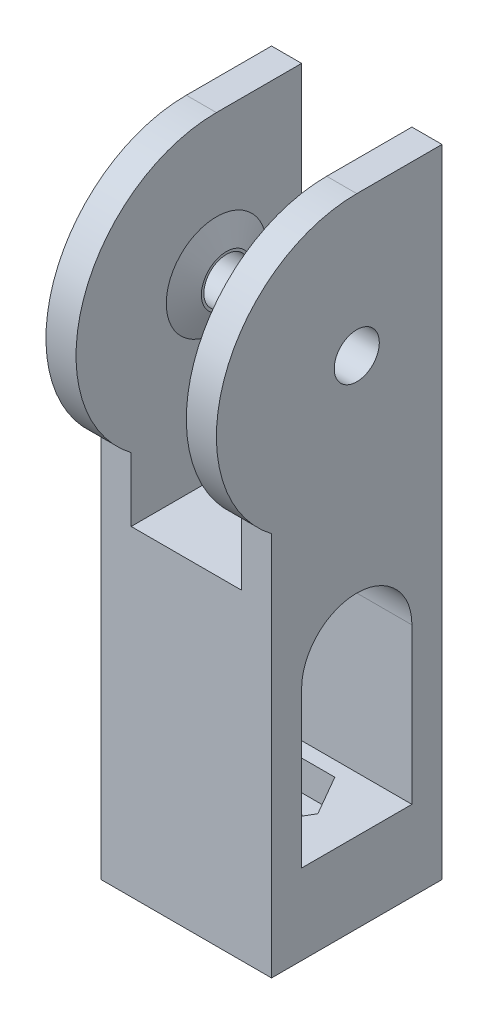
SolidWorks part; units mm, degrees
ref_plane "Front Plane" through (0, 0, 0) normal (0, 0, 1) x (1, 0, 0)
ref_plane "Top Plane" through (0, 0, 0) normal (0, 1, 0) x (1, 0, 0)
ref_plane "Right Plane" through (0, 0, 0) normal (1, 0, 0) x (0, 0, -1)
sketch "Sketch1" plane through (0, 0, 0) normal (0, 0, 1) x (1, 0, 0)
  line L0 (8.5, 32) -> (8.5, 0) construction
  line L1 (0, 0) -> (17, 0)
  line L2 (0, 0) -> (0, 63.5)
  line L3 (0, 63.5) -> (3, 63.5)
  line L4 (17, 0) -> (17, 63.5)
  line L5 (14, 63.5) -> (17, 63.5)
  line L6 (3, 63.5) -> (3, 32)
  line L7 (3, 32) -> (14, 32)
  line L8 (14, 63.5) -> (14, 32)
  dimension "D1" = 63.5
  dimension "D2" = 17
  dimension "D3" = 11
  dimension "D4" = 31.5
extrude "Boss-Extrude1" add sketch "Sketch1" along normal blind 22.5
sketch "Sketch2" plane through (17, 0, 0) normal (1, 0, 0) x (0, 0, -1)
  line L0 (-8.5, 8) -> (-8.5, 0) construction
  line L1 (-14, 23.5) -> (-3, 23.5) construction
  line L2 (-14, 23.5) -> (-14, 8)
  line L3 (-14, 8) -> (-3, 8)
  line L4 (-3, 23.5) -> (-3, 8)
  line L6 (-22.5, 0) -> (0, 0) construction
  line L7 (-8.5, 23.5) -> (-8.5, 49.5) construction
  line L8 (0, 0) -> (0, 63.5) construction
  line L9 (-22.5, 63.5) -> (-8.5, 63.5)
  line L10 (-22.5, 63.5) -> (0, 63.5) construction
  line L11 (-22.5, 63.5) -> (-22.5, 49.5)
  line L12 (-22.5, 0) -> (-22.5, 63.5) construction
  line L13 (-22.5, 0) -> (-22.5, 49.5)
  line L14 (-17, 38.3757) -> (-17, 0)
  line L15 (-22.5, 0) -> (-17, 0)
  arc A0 (-14, 23.5) -> (-3, 23.5) centre (-8.5, 23.5) cw
  circle A1 centre (-8.5, 49.5) radius 4.25 construction
  arc A2 (-8.5, 63.5) -> (-17, 38.3757) centre (-8.5, 49.5) ccw
  point P29 (-17, 19.1879)
  line M9 (0, 63.5) -> (-22.5, 63.5)
  line M10 (-22.5, 63.5) -> (-22.5, 0)
  line M11 (-22.5, 0) -> (0, 0)
  dimension "D3" = 5.5
  dimension "D5" = 8.5
  dimension "D7" = 28
  dimension "D1" = 11
  dimension "D2" = 15.5
  dimension "D4" = 8
  dimension "D6" = 26
  dimension "D8" = 8.5
  dimension "D9" = 5.5
extrude "Cut-Extrude1" cut sketch "Sketch2" against normal through all contours A2 L14 M10 M11 | A2 M9 M10 | A0 L2 L3 L4 | A1
sketch "Sketch3" plane through (0, 0, 0) normal (0, -1, 0) x (1, 0, 0)
  line L0 (0, 0) -> (17, 17) construction
  circle A0 centre (8.5, 8.5) radius 2.3
  dimension "D1" = 4.6
extrude "Cut-Extrude2" cut sketch "Sketch3" against normal up to surface (8 mm away) up to face at (8.5, 8, 8.5)
sketch "Sketch4" plane through (0, 8, 0) normal (0, 1, 0) x (1, 0, 0)
  line L1 (3.8812, -8.5) -> (6.1906, -12.5)
  line L2 (6.1906, -12.5) -> (10.8094, -12.5)
  line L3 (10.8094, -12.5) -> (13.1188, -8.5)
  line L4 (13.1188, -8.5) -> (10.8094, -4.5)
  line L5 (10.8094, -4.5) -> (6.1906, -4.5)
  line L6 (6.1906, -4.5) -> (3.8812, -8.5)
  circle A0 centre (8.5, -8.5) radius 4 construction
  dimension "D1" = 8
extrude "Cut-Extrude3" cut sketch "Sketch4" against normal blind 3
sketch "Sketch5" plane through (14, 0, 0) normal (-1, 0, 0) x (0, 0, 1)
  circle A0 centre (8.5, 49.5) radius 5
  dimension "D1" = 10
ref_plane "Plane1" through (13, 0, 0) normal (-1, 0, 0) x (0, 0, 1)
sketch "Sketch6" plane through (13, 0, 0) normal (-1, 0, 0) x (0, 0, 1)
  circle A0 centre (8.5, 49.5) radius 2.5
  dimension "D1" = 5
loft "Loft1" add profiles "Sketch5", "Sketch6"
ref_plane "Plane2" through (8.5, 0, 0) normal (-1, 0, 0) x (0, 0, 1)
mirror "Mirror1" about plane through (8.5, 0, 0) normal (-1, 0, 0) of "Loft1"
sketch "Sketch7" plane through (17, 0, 0) normal (1, 0, 0) x (0, 0, -1)
  circle A0 centre (-8.5, 49.5) radius 4.25 construction
  dimension "D1" = 8.5
hole_wizard "M4 Clearance Hole1" positions "3DSketch1" profile "Sketch8" hole size "M4" standard "ANSI Metric" end condition through all
sketch3d "3DSketch1"
  point P0 (17, 49.5, 8.5)
sketch "Sketch8" plane through (17, 49.5, 8.5) normal (0, 1, 0) x (0, 0, -1)
  line L0 (0, 0) -> (0, 17)
  line L1 (0, 17) -> (2.25, 17)
  line L2 (2.25, 17) -> (2.25, 0)
  line L5 (2.25, 0) -> (0, 0)
  line L11 (0, -6.35) -> (0, 107.95) construction
  dimension "Thru Hole Dia." = 4.5
  dimension "Thru Hole Depth" = 17
